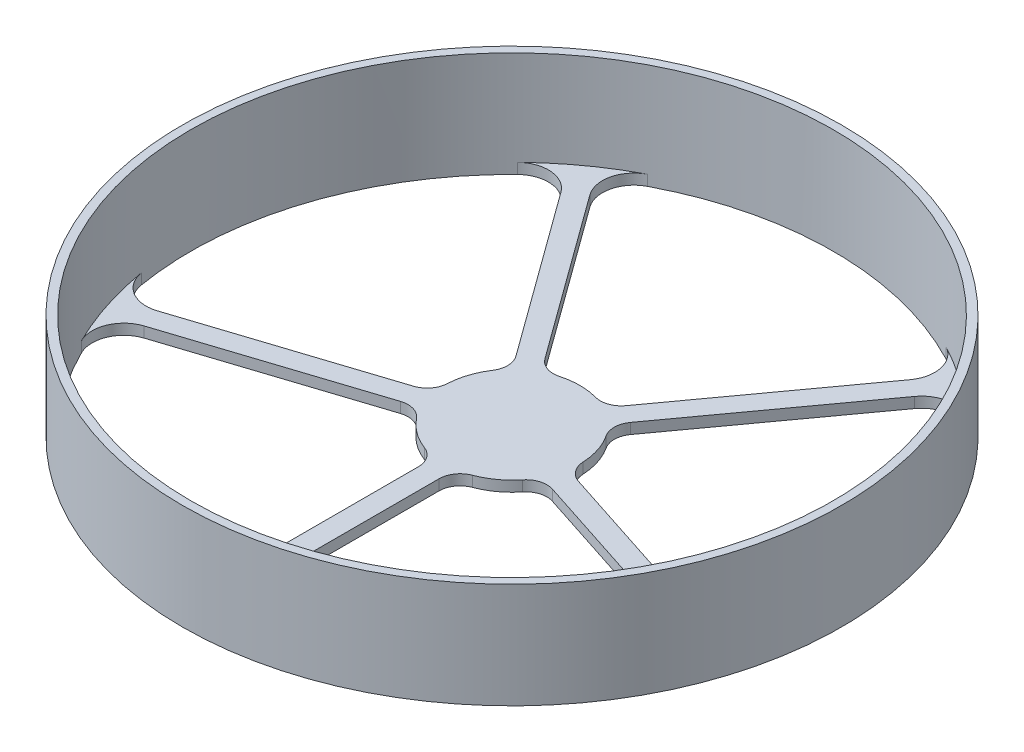
SolidWorks part; units mm, degrees
ref_plane "Front Plane" through (0, 0, 0) normal (0, 0, 1) x (1, 0, 0)
ref_plane "Top Plane" through (0, 0, 0) normal (0, 1, 0) x (1, 0, 0)
ref_plane "Right Plane" through (0, 0, 0) normal (1, 0, 0) x (0, 0, -1)
sketch "Sketch1" plane through (0, 0, 0) normal (0, 1, 0) x (1, 0, 0)
  line L12 (7.4949, 14.5691) -> (43.5132, 64.144)
  line L13 (11.54, 11.6302) -> (47.5583, 61.2051)
  line L14 (43.5132, 64.144) -> (47.5583, 61.2051)
  line L16 (16.1721, -2.626) -> (74.4509, -21.5619)
  line L17 (74.4509, -21.5619) -> (72.9058, -26.3172)
  line L18 (14.627, -7.3813) -> (72.9058, -26.3172)
  line L20 (2.5, -16.1921) -> (2.5, -77.47)
  line L21 (2.5, -77.47) -> (-2.5, -77.47)
  line L22 (-2.5, -16.1921) -> (-2.5, -77.47)
  line L24 (-14.627, -7.3813) -> (-72.9058, -26.3172)
  line L25 (-72.9058, -26.3172) -> (-74.4509, -21.5619)
  line L26 (-16.1721, -2.626) -> (-74.4509, -21.5619)
  line L28 (-11.54, 11.6302) -> (-47.5583, 61.2051)
  line L29 (-47.5583, 61.2051) -> (-43.5132, 64.144)
  line L30 (-7.4949, 14.5691) -> (-43.5132, 64.144)
  circle A0 centre (0, 0) radius 16.3839
  point P3 (7.791, 10.7234)
  point P12 (45.5357, 62.6745)
  point P33 (0, 0)
  dimension "D1" = 77.47
  dimension "D2" = 5
  dimension "D3" = 5
extrude "Boss-Extrude1" add sketch "Sketch1" along normal blind 2.54 contours A0 | A0 L30 L29 L28 | A0 L13 L14 L12 | A0 L18 L17 L16 | A0 L22 L21 L20 | A0 L26 L25 L24
sketch "Sketch2" plane through (0, 0, 0) normal (0, 1, 0) x (1, 0, 0)
  circle A0 centre (0, 0) radius 77.47
  circle A1 centre (0, 0) radius 79.4512
extrude "Boss-Extrude2" add sketch "Sketch2" along normal blind 25.4
fillet "Fillet2" radius 7.62 10 edges at (72.8674, 1.27, 26.3047) (74.4125, 1.27, 21.5494) (2.5, 1.27, 77.4297) (-2.5, 1.27, 77.4297) (-72.8674, 1.27, 26.3047) (-74.4125, 1.27, 21.5494) (-47.5345, 1.27, -61.1724) (-43.4895, 1.27, -64.1114) (43.4895, 1.27, -64.1114) (47.5345, 1.27, -61.1724)
fillet "Fillet3" radius 5.08 10 edges at (-7.4949, 1.27, -14.5691) (7.4949, 1.27, -14.5691) (-11.54, 1.27, -11.6302) (-16.1721, 1.27, 2.626) (-14.627, 1.27, 7.3813) (-2.5, 1.27, 16.1921) (2.5, 1.27, 16.1921) (14.627, 1.27, 7.3813) (16.1721, 1.27, 2.626) (11.54, 1.27, -11.6302)
ref_plane "Plane1" through (79.4512, 0, 0) normal (1, 0, 0) x (0, 0, -1)
sketch "Sketch4" plane through (79.4512, 0, 0) normal (1, 0, 0) x (0, 0, -1)
  line L0 (79.4512, 25.4) -> (-79.4512, 25.4) construction
  line L1 (-441.6214, 25.4) -> (57.5852, 25.4)
  line L2 (-441.6214, 25.4) -> (-441.6214, 0)
  line L3 (-441.6214, 0) -> (57.5852, 0)
  line L5 (-441.6214, 12.7) -> (57.5852, 12.7) construction
  line L6 (-436.5814, 30.48) -> (-418.7331, 30.48)
  line L7 (-439.1214, 27.94) -> (-439.1214, 7.62)
  line L8 (-436.5814, 5.08) -> (-418.7331, 5.08)
  line L9 (-416.1931, 27.94) -> (-416.1931, 7.62)
  line L102 (57.5852, 25.4) -> (57.5852, 0)
  arc A0 (-436.5814, 30.48) -> (-439.1214, 27.94) centre (-436.5814, 27.94) ccw
  arc A1 (-439.1214, 7.62) -> (-436.5814, 5.08) centre (-436.5814, 7.62) ccw
  arc A2 (-418.7331, 5.08) -> (-416.1931, 7.62) centre (-418.7331, 7.62) ccw
  arc A3 (-418.7331, 30.48) -> (-416.1931, 27.94) centre (-418.7331, 27.94) cw
  point P11 (-416.1931, 17.78)
  point P19 (-439.1214, 5.08)
  point P24 (-416.1931, 30.48)
  dimension "D4" = 2.54
  dimension "D1" = 499.2066
  dimension "D2" = 2.5
  dimension "D3" = 12.7
  dimension "D5" = 22.9283
equation "\"D1@Sketch4\"=6.256*PI"
